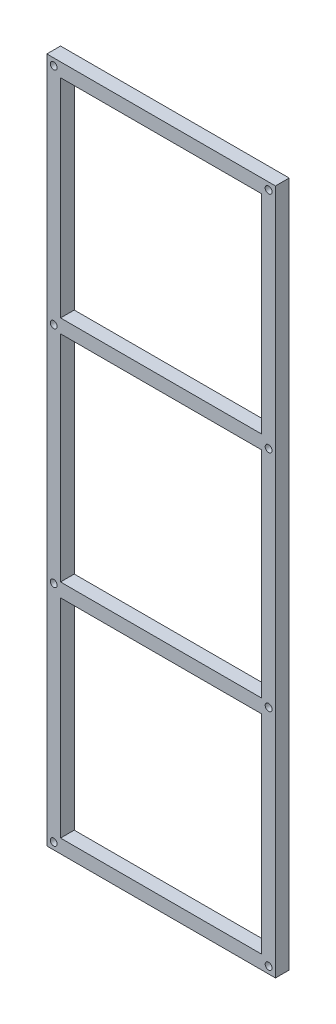
SolidWorks part; units mm, degrees
ref_plane "Front Plane" through (0, 0, 0) normal (0, 0, 1) x (1, 0, 0)
ref_plane "Top Plane" through (0, 0, 0) normal (0, 1, 0) x (1, 0, 0)
ref_plane "Right Plane" through (0, 0, 0) normal (1, 0, 0) x (0, 0, -1)
sketch "Sketch1" plane through (0, 0, 0) normal (0, 0, 1) x (1, 0, 0)
  line L0 (44, 144) -> (44, 53)
  line L9 (-50, -150) -> (50, -150)
  line L10 (-50, -150) -> (-50, 150)
  line L11 (-50, 150) -> (50, 150)
  line L12 (50, -150) -> (50, 150)
  line L15 (-44, -144) -> (44, -144)
  line L16 (-44, -144) -> (-44, -53)
  line L17 (-44, 144) -> (44, 144)
  line L21 (-44, 53) -> (44, 53)
  line L23 (-44, 47) -> (44, 47)
  line L25 (-44, -47) -> (44, -47)
  line L27 (-44, -53) -> (44, -53)
  line L33 (44, 47) -> (44, -47)
  line L34 (-44, 53) -> (-44, 144)
  line L35 (-44, -47) -> (-44, 47)
  line L36 (44, -53) -> (44, -144)
  point P0 (0, 0)
  point P6 (0, 0)
  point P20 (0, 0)
  dimension "D1" = 100
  dimension "D2" = 300
  dimension "D3" = 88
  dimension "D4" = 288
  dimension "D5" = 6
  dimension "D6" = 91
  dimension "D7" = 6
  dimension "D8" = 91
extrude "Boss-Extrude1" add sketch "Sketch1" along normal blind 6
sketch "Sketch2" plane through (0, 0, 6) normal (0, 0, 1) x (1, 0, 0)
  line L0 (-50, 150) -> (-44, 144)
  line L1 (44, 144) -> (50, 150)
  line L2 (44, -144) -> (50, -150)
  line L3 (-44, -144) -> (-50, -150)
  circle A0 centre (-47, 147) radius 1.5
  circle A1 centre (47, 147) radius 1.5
  circle A2 centre (47, 49) radius 1.5
  circle A3 centre (47, -49) radius 1.5
  circle A4 centre (47, -147) radius 1.5
  circle A5 centre (-47, 49) radius 1.5
  circle A6 centre (-47, -49) radius 1.5
  circle A7 centre (-47, -147) radius 1.5
  point P18 (47, 147)
  point P19 (-47, -147)
  dimension "D1" = 94
  dimension "D2" = 294
  dimension "D3" = 2
  dimension "D4" = 4
extrude "Cut-Extrude1" cut sketch "Sketch2" against normal blind 6 contours A0 | A1 | A5 | A2 | A6 | A3 | A7 | A4
